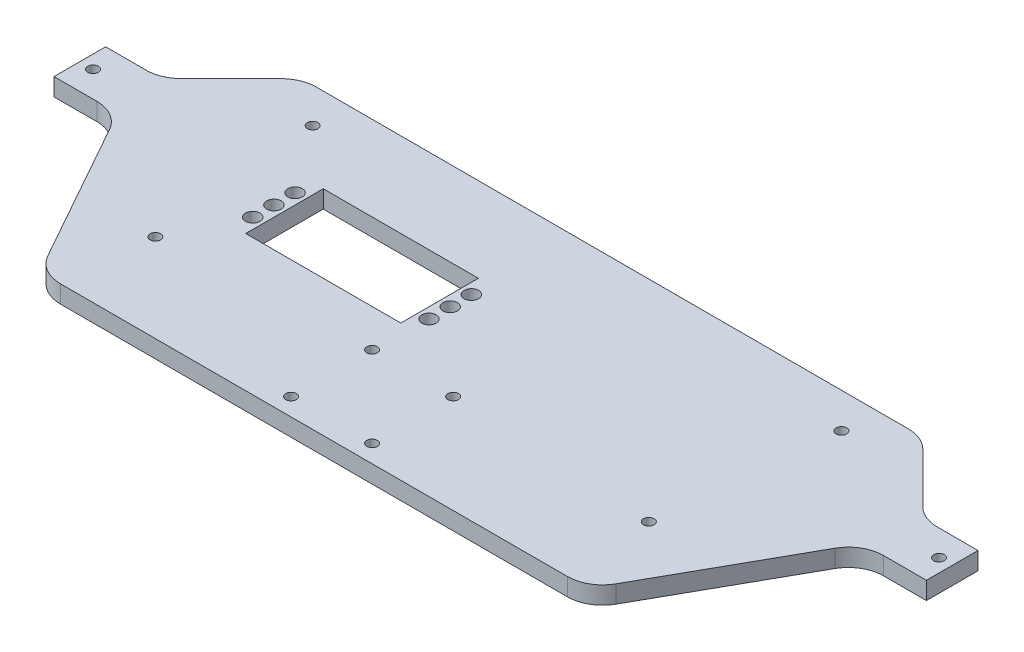
SolidWorks part; units mm, degrees
ref_plane "Alzado" through (0, 0, 0) normal (0, 0, 1) x (1, 0, 0)
ref_plane "Planta" through (0, 0, 0) normal (0, 1, 0) x (1, 0, 0)
ref_plane "Vista lateral" through (0, 0, 0) normal (1, 0, 0) x (0, 0, -1)
sketch "Croquis1" plane through (0, 0, 0) normal (0, 1, 0) x (1, 0, 0)
  line L0 (-27.8825, 0) -> (38.5584, 0) construction
  line L1 (-88.1, 42.3182) -> (88.1, 42.3182)
  line L2 (-77.75, -42.3182) -> (77.75, -42.3182)
  line L3 (-88.1, 42.3182) -> (-108.1, 22.3182)
  line L4 (-108.1, 22.3182) -> (-127.75, 22.3182)
  line L5 (0, 0) -> (0, 27.7067) construction
  line L6 (-127.75, 22.3182) -> (-127.75, 7.6818)
  line L7 (-127.75, 7.6818) -> (-105.75, 7.6818)
  line L8 (-105.75, 7.6818) -> (-77.75, -42.3182)
  line L9 (88.1, 42.3182) -> (108.1, 22.3182)
  line L10 (108.1, 22.3182) -> (127.75, 22.3182)
  line L11 (127.75, 22.3182) -> (127.75, 7.6818)
  line L12 (127.75, 7.6818) -> (105.75, 7.6818)
  line L13 (105.75, 7.6818) -> (77.75, -42.3182)
  dimension "D1" = 255.5
  dimension "D2" = 84.6363
  dimension "D3" = 19.65
  dimension "D4" = 22
  dimension "D5" = 22
  dimension "D6" = 50
  dimension "D7" = 50
  dimension "D8" = 50
  dimension "D9" = 20
  dimension "D10" = 20
  dimension "D11" = 19.65
extrude "Saliente-Extruir1" add sketch "Croquis1" along normal blind 5
fillet "Redondeo1" radius 10 8 edges at (88.1, 2.5, -42.3182) (-88.1, 2.5, -42.3182) (-77.75, 2.5, 42.3182) (77.75, 2.5, 42.3182) (108.1, 2.5, -22.3182) (105.75, 2.5, -7.6818) (-105.75, 2.5, -7.6818) (-108.1, 2.5, -22.3182)
sketch "Croquis2" plane through (0, 5, 0) normal (0, 1, 0) x (1, 0, 0)
  line L0 (0, 0) -> (0, -87.7887) construction
  line L1 (-119.9961, 22.3182) -> (-119.9961, 40.4374) construction
  line L2 (-112.2421, 22.3182) -> (-127.75, 22.3182) construction
  line L3 (-127.75, 15) -> (-123.2915, 15) construction
  line L4 (-127.75, 22.3182) -> (-127.75, 7.6818) construction
  line L5 (119.9961, 22.3182) -> (119.9961, 29.1715) construction
  line L6 (127.75, 22.3182) -> (112.2421, 22.3182) construction
  line L7 (115.6048, 15) -> (126.3231, 15) construction
  line L8 (83.9579, 42.3182) -> (-83.9579, 42.3182) construction
  line L9 (-57, 17.3182) -> (-15, 17.3182)
  line L10 (-71.8888, -42.3182) -> (71.8888, -42.3182) construction
  line L11 (-15, 17.3182) -> (-15, -2.6818)
  line L12 (-15, -2.6818) -> (-57, -2.6818)
  line L13 (-57, -2.6818) -> (-57, 17.3182)
  line L14 (-57, 7.3182) -> (-2.6959, 7.3182) construction
  line L15 (-36, 17.3182) -> (-36, 33.9331) construction
  line L16 (-11, 7.3182) -> (-11, 14.1752) construction
  line L17 (-61, 7.3182) -> (-61, 4.4352) construction
  circle A0 centre (70, -17.3182) radius 1.5
  circle A1 centre (-70, -17.3182) radius 1.5
  circle A2 centre (-119.9961, 15) radius 1.5
  circle A3 centre (119.9961, 15) radius 1.5
  circle A4 centre (-75, 32.3182) radius 1.5
  circle A5 centre (75, 32.3182) radius 1.5
  circle A6 centre (-11.5, -14.3182) radius 1.5
  circle A7 centre (11.5, -14.3182) radius 1.5
  circle A8 centre (-11.5, -37.3182) radius 1.5
  circle A9 centre (11.5, -37.3182) radius 1.5
  circle A10 centre (-61, 7.3182) radius 2.05
  circle A11 centre (-11, 7.3182) radius 2.05
  circle A12 centre (-61, 13.3182) radius 2.05
  circle A13 centre (-61, 1.3182) radius 2.05
  circle A14 centre (-11, 13.3182) radius 2.05
  circle A15 centre (-11, 1.3182) radius 2.05
  dimension "D1" = 3
  dimension "D2" = 3
  dimension "D7" = 3
  dimension "D8" = 3
  dimension "D10" = 3
  dimension "D11" = 3
  dimension "D17" = 3
  dimension "D18" = 3
  dimension "D19" = 3
  dimension "D20" = 3
  dimension "D25" = 50
  dimension "D27" = 4.1
  dimension "D28" = 4.1
  dimension "D29" = 4.1
  dimension "D30" = 4.1
  dimension "D31" = 4.1
  dimension "D32" = 4.1
  dimension "D3" = 75
  dimension "D4" = 75
  dimension "D5" = 10
  dimension "D6" = 10
  dimension "D9" = 140
  dimension "D12" = 25
  dimension "D13" = 23
  dimension "D14" = 23
  dimension "D15" = 5
  dimension "D16" = 23
  dimension "D21" = 42
  dimension "D22" = 20
  dimension "D23" = 30
  dimension "D24" = 25
  dimension "D26" = 50
  dimension "D33" = 6
  dimension "D34" = 6
  dimension "D35" = 6
  dimension "D36" = 6
extrude "Cortar-Extruir1" cut sketch "Croquis2" against normal through all
sketch "Croquis3" plane through (0, 5, 0) normal (0, 1, 0) x (1, 0, 0)
  line L0 (-123.75, 22.3182) -> (-123.75, 7.6818)
  line L1 (-112.2421, 22.3182) -> (-127.75, 22.3182) construction
  line L2 (-127.75, 7.6818) -> (-111.6112, 7.6818) construction
  line L3 (-123.75, 7.6818) -> (-127.75, 7.6818)
  line L4 (-127.75, 7.6818) -> (-127.75, 22.3182)
  line L5 (-127.75, 22.3182) -> (-123.75, 22.3182)
  line L6 (127.75, 7.6818) -> (127.75, 22.3182)
  line L7 (127.75, 22.3182) -> (123.75, 22.3182)
  line L8 (127.75, 22.3182) -> (112.2421, 22.3182) construction
  line L9 (123.75, 22.3182) -> (123.75, 7.6818)
  line L10 (111.6112, 7.6818) -> (127.75, 7.6818) construction
  line L11 (123.75, 7.6818) -> (127.75, 7.6818)
  dimension "D1" = 4
  dimension "D2" = 4
extrude "Cortar-Extruir2" cut sketch "Croquis3" against normal through all
sketch "Croquis4" plane through (0, 5, 0) normal (0, 1, 0) x (1, 0, 0)
  line L0 (-36, 17.3182) -> (-36, -16.9775) construction
  line L1 (-15, 17.3182) -> (-57, 17.3182) construction
  line L2 (-57, 7.3182) -> (-47.1795, 7.3182) construction
  line L3 (-57, 17.3182) -> (-57, -2.6818) construction
  line L4 (-58, 18.3182) -> (-58, -3.6818)
  line L5 (-58, -3.6818) -> (-14, -3.6818)
  line L6 (-14, -3.6818) -> (-14, 18.3182)
  line L7 (-58, 18.3182) -> (-14, 18.3182)
  line L8 (-15, -2.6818) -> (-15, 17.3182) construction
  line L9 (-57, -2.6818) -> (-15, -2.6818) construction
  dimension "D1" = 1
  dimension "D2" = 1
  dimension "D3" = 1
  dimension "D4" = 1
extrude "Cortar-Extruir3" cut sketch "Croquis4" against normal through all
